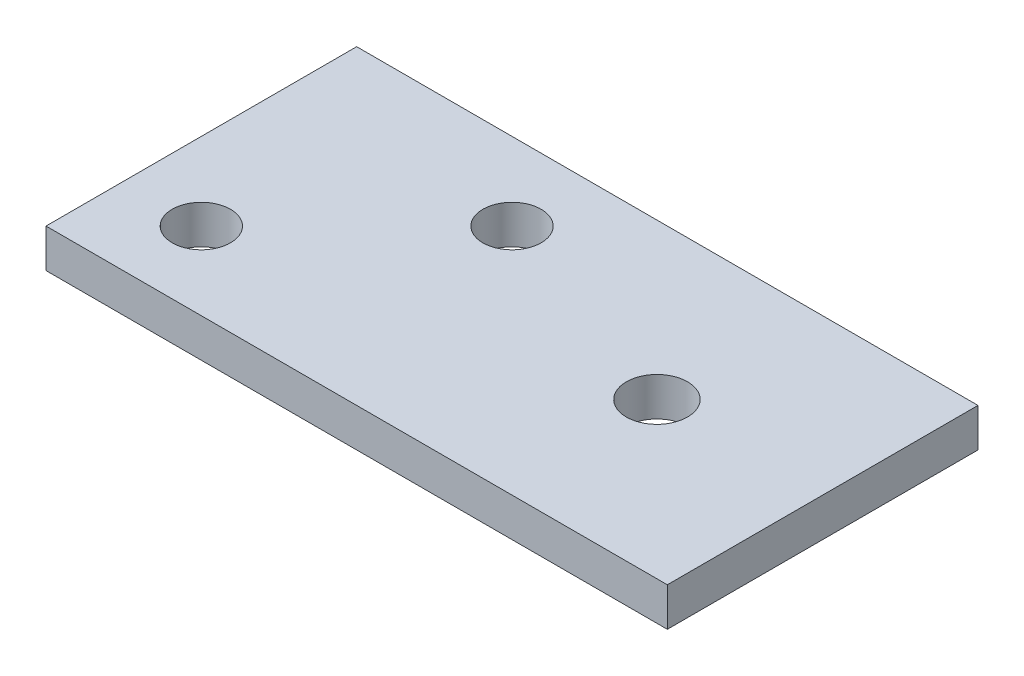
SolidWorks part; units mm, degrees
ref_plane "Alzado" through (0, 0, 0) normal (0, 0, 1) x (1, 0, 0)
ref_plane "Planta" through (0, 0, 0) normal (0, 1, 0) x (1, 0, 0)
ref_plane "Vista lateral" through (0, 0, 0) normal (1, 0, 0) x (0, 0, -1)
sketch "Croquis1" plane through (0, 0, 0) normal (0, 1, 0) x (1, 0, 0)
  line L1 (-50.8, 25.4) -> (50.8, 25.4)
  line L2 (-50.8, 25.4) -> (-50.8, -25.4)
  line L3 (-50.8, -25.4) -> (50.8, -25.4)
  line L4 (50.8, 25.4) -> (50.8, -25.4)
  line L5 (-50.8, 25.4) -> (50.8, -25.4) construction
  line L6 (-50.8, -25.4) -> (50.8, 25.4) construction
  point P0 (0, 0)
  dimension "D1" = 101.6
  dimension "D2" = 50.8
extrude "Saliente-Extruir1" add sketch "Croquis1" along normal blind 6.31
sketch "Croquis2" plane through (0, 6.31, 0) normal (0, 1, 0) x (1, 0, 0)
  line L0 (-50.8, 0) -> (50.8, 0) construction
  line L1 (-50.8, 25.4) -> (-50.8, -25.4) construction
  line L2 (50.8, -25.4) -> (50.8, 25.4) construction
  line L3 (50.8, 0) -> (0, 0) construction
  line L4 (0, 0) -> (25.4, 0) construction
  line L5 (25.4, 0) -> (25.4, 7.5763) construction
  line L6 (0, 0) -> (-50.8, 0) construction
  line L7 (-50.8, 0) -> (-25.4, 0) construction
  line L8 (-25.4, 0) -> (-25.4, 7.5763) construction
  line L9 (-25.4, 7.5763) -> (-18.1136, 12.9756) construction
  line L10 (-25.4, 0) -> (-50.8, -25.4) construction
  line L11 (-50.8, -25.4) -> (-25.4, 0) construction
  line L12 (0, 0) -> (0, 25.4) construction
  line L13 (50.8, 25.4) -> (-50.8, 25.4) construction
  line L14 (-25.4, 0) -> (-38.1, -12.7) construction
  line L15 (-38.1, -12.7) -> (-27.7316, -12.7) construction
  line L16 (-25.4, 0) -> (0, 25.4) construction
  line L17 (0, 25.4) -> (-12.7, 12.7) construction
  line L18 (-12.7, 12.7) -> (-7.8781, 12.7) construction
  circle A0 centre (-38.1, -12.7) radius 4.7625
  circle A1 centre (-12.7, 12.7) radius 4.7625
  dimension "D2" = 9.525
  dimension "D3" = 9.525
  dimension "D1" = 45
extrude "Cortar-Extruir1" cut sketch "Croquis2" against normal blind 6.31
sketch "Croquis3" plane through (0, 6.31, 0) normal (0, 1, 0) x (1, 0, 0)
  line L0 (17.118, 9.0161) -> (25.4, 0) construction
  line L1 (25.4, 0) -> (25.4, 4.765) construction
  line L2 (25.4, 0) -> (50.8, 0) construction
  line L3 (50.8, -25.4) -> (50.8, 25.4) construction
  line L4 (50.8, 0) -> (23.7, 0) construction
  circle A0 centre (25.4, 0) radius 4.765 construction
  circle A1 centre (25.4, 0) radius 5 construction
  circle A2 centre (23.7, 0) radius 5
  dimension "D1" = 10
  dimension "D3" = 10
  dimension "D2" = 27.1
extrude "Cortar-Extruir2" cut sketch "Croquis3" against normal blind 10
